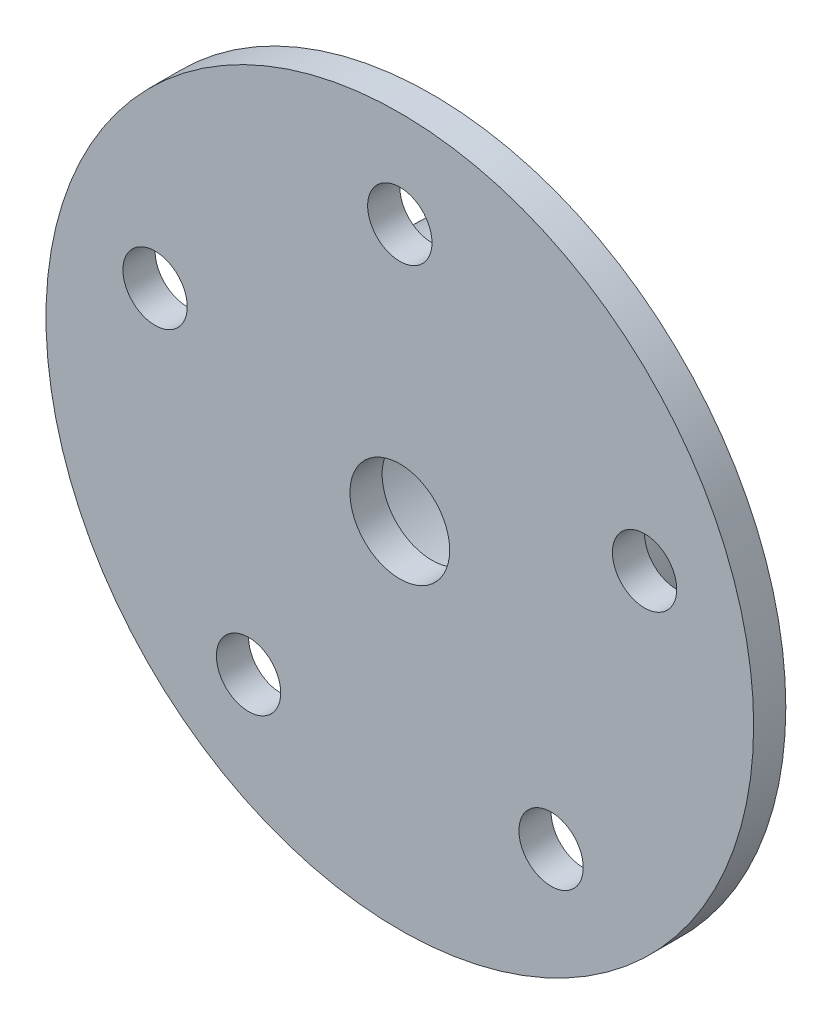
SolidWorks part; units mm, degrees
ref_plane "前视基准面" through (0, 0, 0) normal (0, 0, 1) x (1, 0, 0)
ref_plane "上视基准面" through (0, 0, 0) normal (0, 1, 0) x (1, 0, 0)
ref_plane "右视基准面" through (0, 0, 0) normal (1, 0, 0) x (0, 0, -1)
other "Configuration Table"
sketch "草图1" plane through (0, 0, 0) normal (0, 0, 1) x (1, 0, 0)
  circle A4 centre (0, 0) radius 3.1
  circle A5 centre (0, 0) radius 22
  circle A6 centre (0, 0) radius 16 construction
  circle A8 centre (0, 16) radius 2
  circle A9 centre (15.2169, 4.9443) radius 2
  circle A10 centre (9.4046, -12.9443) radius 2
  circle A11 centre (-9.4046, -12.9443) radius 2
  circle A12 centre (-15.2169, 4.9443) radius 2
  point P0 (0, 0)
  point P17 (0, 0)
  point P19 (0, 0)
  dimension "D3" = 5
  dimension "D1" = 44
  dimension "D2" = 32
  dimension "D4" = 6.2
extrude "凸台-拉伸1" add sketch "草图1" along normal blind 2
sketch "草图3" plane through (0, 0, 0) normal (0, 0, -1) x (-1, 0, 0)
  circle A0 centre (0, 0) radius 11
  circle A1 centre (0, 0) radius 7.6
  dimension "D1" = 22
  dimension "D2" = 15.2
extrude "凸台-拉伸2" add sketch "草图3" along normal blind 7
